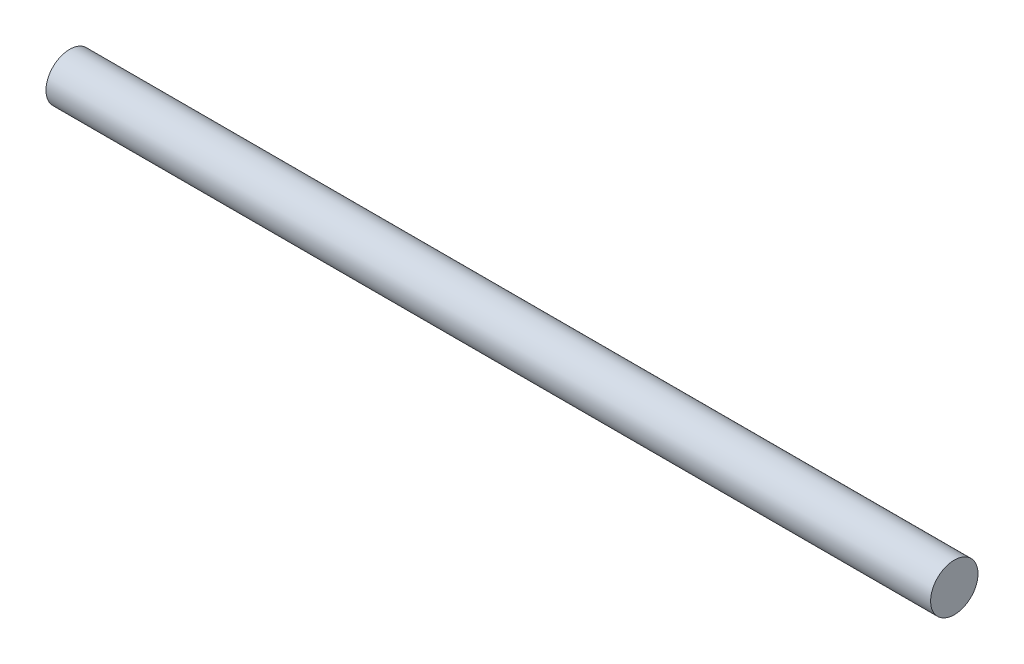
SolidWorks part; units mm, degrees
ref_plane "Front Plane" through (0, 0, 0) normal (0, 0, 1) x (1, 0, 0)
ref_plane "Top Plane" through (0, 0, 0) normal (0, 1, 0) x (1, 0, 0)
ref_plane "Right Plane" through (0, 0, 0) normal (1, 0, 0) x (0, 0, -1)
sketch "Sketch2" plane through (0, 0, 0) normal (1, 0, 0) x (0, 0, -1)
  circle A0 centre (0, 0) radius 15
  dimension "D1" = 30
extrude "Boss-Extrude2" add sketch "Sketch2" along normal blind 560
